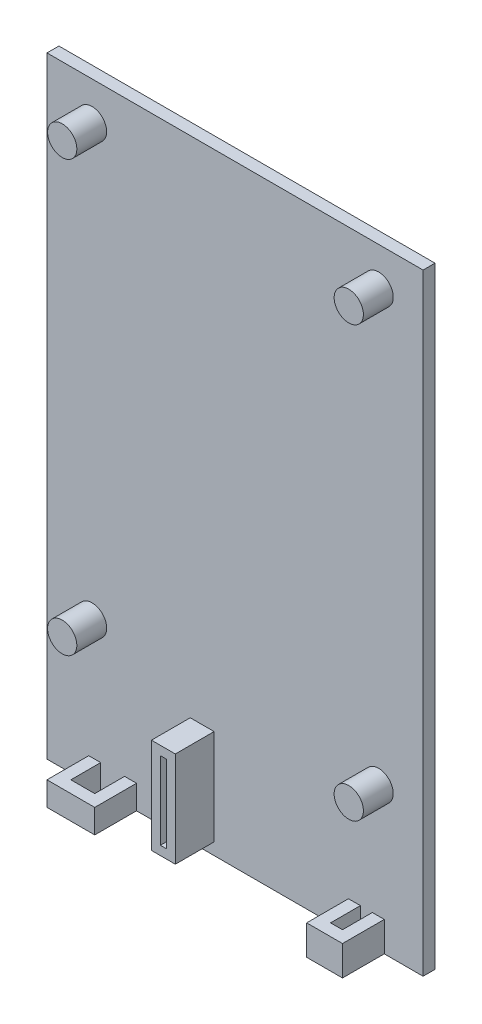
SolidWorks part; units mm, degrees
ref_plane "Přední rovina" through (0, 0, 0) normal (0, 0, 1) x (1, 0, 0)
ref_plane "Horní rovina" through (0, 0, 0) normal (0, 1, 0) x (1, 0, 0)
ref_plane "Pravá rovina" through (0, 0, 0) normal (1, 0, 0) x (0, 0, -1)
sketch "Skica1" plane through (0, 0, 0) normal (0, 0, 1) x (1, 0, 0)
  line L0 (13, -102.45) -> (13, -115.45)
  line L1 (0, 0) -> (63, 0)
  line L2 (0, 0) -> (0, -102.45)
  line L3 (0, -102.45) -> (13, -102.45)
  line L4 (63, 0) -> (63, -102.45)
  line L5 (13, -115.45) -> (50, -115.45)
  line L6 (50, -115.45) -> (50, -102.45)
  line L7 (50, -102.45) -> (63, -102.45)
  dimension "D1" = 102.45
  dimension "D2" = 63
  dimension "D3" = 13
  dimension "D4" = 13
  dimension "D5" = 13
extrude "Přidat vysunutím1" add sketch "Skica1" along normal blind 2
sketch "Skica3" plane through (0, 0, 2) normal (0, 0, 1) x (1, 0, 0)
  line L0 (63, -102.45) -> (63, 0) construction
  line L1 (63, 0) -> (0, 0) construction
  circle A0 centre (7.55, -6.45) radius 2.45
  circle A1 centre (7.55, -78.45) radius 2.45
  circle A2 centre (55.55, -78.45) radius 2.45
  circle A3 centre (55.55, -6.45) radius 2.45
  dimension "D1" = 4.9
  dimension "D2" = 48
  dimension "D4" = 7.45
  dimension "D5" = 6.45
  dimension "D3" = 72
extrude "Přidat vysunutím3" add sketch "Skica3" along normal blind 5
sketch "Skica4" plane through (0, 0, 2) normal (0, 0, 1) x (1, 0, 0)
  line L4 (63, 0) -> (63, -102.45)
  line L5 (3, -3) -> (60, -3)
  line L8 (60, -3) -> (60, -102.45)
  line L10 (60, -102.45) -> (63, -102.45)
  line L12 (0, 0) -> (0, -102.45)
  line L13 (0, 0) -> (63, 0)
  line L17 (3, -3) -> (3, -102.45)
  line L18 (0, -102.45) -> (13, -102.45) construction
  line L19 (3, -102.45) -> (0, -102.45)
  dimension "D1" = 3
  dimension "D2" = 3
  dimension "D3" = 3
extrude "Přidat vysunutím4" add sketch "Skica4" along normal blind 37.5
sketch "Skica8" plane through (60, 0, 0) normal (-1, 0, 0) x (0, 0, 1)
  line L0 (39.5, -3) -> (2, -3) construction
  line L1 (2, -54) -> (12, -54)
  line L2 (2, -54) -> (2, -44)
  line L3 (2, -44) -> (12, -44)
  line L4 (12, -54) -> (12, -44)
  line L5 (2, -3) -> (2, -102.45) construction
  dimension "D1" = 10
  dimension "D2" = 10
  dimension "D3" = 41
extrude "Odebrat vysunutím2" cut sketch "Skica8" against normal through all
sketch "Skica10" plane through (0, 0, 0) normal (-1, 0, 0) x (0, 0, 1)
  line L1 (12, -82) -> (39.5, -82)
  line L2 (12, -82) -> (12, -3)
  line L3 (12, -3) -> (39.5, -3)
  line L4 (39.5, -82) -> (39.5, -3)
  line L5 (39.5, 0) -> (39.5, -102.45) construction
  line L6 (0, 0) -> (0, -102.45) construction
  line L7 (39.5, 0) -> (0, 0) construction
  dimension "D1" = 3
  dimension "D2" = 12
  dimension "D3" = 79
extrude "Odebrat vysunutím3" cut sketch "Skica10" against normal up to surface (3 mm away) up to face at (3, -52.725, 20.75)
sketch "Skica11" plane through (0, 0, 2) normal (0, 0, 1) x (1, 0, 0)
  line L0 (3, -82) -> (60, -82)
  line L1 (3, -102.45) -> (3, -3) construction
  line L2 (60, -54) -> (60, -102.45) construction
  line L3 (60, -82) -> (60, -102.45)
  line L4 (60, -102.45) -> (50, -102.45)
  line L5 (50, -102.45) -> (50, -115.45)
  line L6 (50, -115.45) -> (13, -115.45)
  line L7 (13, -115.45) -> (13, -102.45)
  line L8 (13, -102.45) -> (13, -115.45) construction
  line L9 (3, -102.45) -> (13, -102.45) construction
  line L10 (13, -102.45) -> (3, -102.45)
  line L11 (3, -102.45) -> (3, -82)
  line L12 (3, -3) -> (60, -3) construction
  dimension "D1" = 79
extrude "Přidat vysunutím5" add sketch "Skica11" along normal blind 1
sketch "Skica12" plane through (0, 0, 3) normal (0, 0, 1) x (1, 0, 0)
  line L0 (3, -82) -> (3, -102.45) construction
  line L1 (15.5, -107.45) -> (21, -107.45)
  line L2 (15.5, -107.45) -> (15.5, -110.45)
  line L3 (15.5, -110.45) -> (21, -110.45)
  line L4 (21, -107.45) -> (21, -110.45)
  line L5 (15.5, -107.45) -> (21, -110.45) construction
  line L6 (15.5, -110.45) -> (21, -107.45) construction
  line L7 (13, -115.45) -> (50, -115.45) construction
  line L10 (15.5, -86.25) -> (15.5, -91.75)
  line L13 (15.5, -94.75) -> (15.5, -100.25)
  line L15 (11.2, -91.75) -> (15.5, -91.75)
  line L16 (11.2, -91.75) -> (11.2, -94.75)
  line L17 (11.2, -94.75) -> (15.5, -94.75)
  line L19 (15.5, -86.25) -> (46.5, -86.25)
  line L20 (46.5, -86.25) -> (46.5, -100.25)
  line L21 (46.5, -100.25) -> (15.5, -100.25)
  line L24 (60, -82) -> (3, -82) construction
  point P0 (18.25, -108.95)
  dimension "D1" = 3
  dimension "D2" = 5.5
  dimension "D4" = 5
  dimension "D5" = 3
  dimension "D6" = 14
  dimension "D7" = 31
  dimension "D8" = 4.3
  dimension "D9" = 7.2
  dimension "D10" = 12.5
  dimension "D11" = 5.5
  dimension "D12" = 4.25
sketch "Skica13" plane through (0, -102.45, 0) normal (0, -1, 0) x (1, 0, 0)
  line L1 (0, 39.5) -> (3, 39.5)
  line L2 (0, 39.5) -> (0, 3)
  line L3 (0, 3) -> (3, 3)
  line L4 (3, 39.5) -> (3, 3)
extrude "Odebrat vysunutím6" cut sketch "Skica13" against normal through all
sketch "Skica14" plane through (0, -102.45, 0) normal (0, -1, 0) x (1, 0, 0)
  line L1 (63, 39.5) -> (60, 39.5)
  line L2 (63, 39.5) -> (63, 3)
  line L3 (63, 3) -> (60, 3)
  line L4 (60, 39.5) -> (60, 3)
extrude "Odebrat vysunutím7" cut sketch "Skica14" against normal through all
sketch "Skica15" plane through (3, 0, 0) normal (-1, 0, 0) x (0, 0, 1)
  line L1 (39.5, 0) -> (3, 0)
  line L2 (39.5, 0) -> (39.5, -3)
  line L3 (39.5, -3) -> (3, -3)
  line L4 (3, 0) -> (3, -3)
extrude "Odebrat vysunutím8" cut sketch "Skica15" against normal through all
sketch "Skica19" plane through (0, 0, 3) normal (0, 0, 1) x (1, 0, 0)
  line L1 (13, -115.45) -> (50, -115.45)
  line L2 (13, -115.45) -> (13, -102.45)
  line L3 (13, -102.45) -> (50, -102.45)
  line L4 (50, -115.45) -> (50, -102.45)
extrude "Odebrat vysunutím9" cut sketch "Skica19" against normal through all
sketch "Skica20" plane through (0, 0, 3) normal (0, 0, 1) x (1, 0, 0)
  line L0 (0, -102.45) -> (63, -102.45)
  line L1 (63, -102.45) -> (63, 0)
  line L2 (63, 0) -> (0, 0)
  line L3 (0, 0) -> (0, -102.45)
  line L4 (3, -3) -> (3, -82)
  line L5 (3, -82) -> (60, -82)
  line L6 (60, -82) -> (60, -3)
  line L7 (60, -3) -> (3, -3)
extrude "Odebrat vysunutím10" cut sketch "Skica20" against normal blind 1
sketch "Skica22" plane through (0, 0, 2) normal (0, 0, 1) x (1, 0, 0)
  line L0 (0, -102.45) -> (63, -102.45) construction
  line L1 (7, -102.45) -> (15, -102.45)
  line L2 (7, -102.45) -> (7, -98.45)
  line L3 (7, -98.45) -> (15, -98.45)
  line L4 (15, -102.45) -> (15, -98.45)
  line L5 (0, 0) -> (0, -102.45) construction
  line L6 (50.5, -102.45) -> (56.5, -102.45)
  line L7 (50.5, -102.45) -> (50.5, -97.45)
  line L8 (50.5, -97.45) -> (56.5, -97.45)
  line L9 (56.5, -102.45) -> (56.5, -97.45)
  dimension "D1" = 8
  dimension "D2" = 4
  dimension "D3" = 35.5
  dimension "D4" = 7
  dimension "D5" = 6
  dimension "D6" = 5
extrude "Přidat vysunutím6" add sketch "Skica22" along normal blind 7
sketch "Skica23" plane through (0, -102.45, 0) normal (0, -1, 0) x (1, 0, 0)
  line L7 (15, 2) -> (50.5, 2) construction
  line L8 (9, 7) -> (13, 7)
  line L9 (9, 7) -> (9, 2)
  line L10 (9, 2) -> (13, 2)
  line L11 (13, 7) -> (13, 2)
  line L12 (15, 9) -> (15, 2) construction
  line L16 (56.5, 2) -> (63, 2) construction
  line L17 (52.5, 7) -> (54.5, 7)
  line L18 (52.5, 7) -> (52.5, 2)
  line L19 (52.5, 2) -> (54.5, 2)
  line L20 (54.5, 7) -> (54.5, 2)
  line L21 (50.5, 9) -> (50.5, 2) construction
  dimension "D1" = 4
  dimension "D2" = 5
  dimension "D3" = 0
  dimension "D4" = 2
  dimension "D5" = 0
  dimension "D6" = 2
  dimension "D7" = 2
  dimension "D8" = 5
extrude "Odebrat vysunutím12" cut sketch "Skica23" against normal blind 5
sketch "Skica25" plane through (0, 0, 2) normal (0, 0, 1) x (1, 0, 0)
  line L0 (50.5, -97.45) -> (50.5, -102.45) construction
  line L1 (25.5, -85.95) -> (26.5, -85.95)
  line L2 (25.5, -85.95) -> (25.5, -98.95)
  line L3 (25.5, -98.95) -> (26.5, -98.95)
  line L4 (26.5, -85.95) -> (26.5, -98.95)
  line L5 (24, -84.45) -> (28, -84.45)
  line L6 (24, -84.45) -> (24, -100.45)
  line L7 (24, -100.45) -> (28, -100.45)
  line L8 (28, -84.45) -> (28, -100.45)
  line L9 (15, -102.45) -> (50.5, -102.45) construction
  dimension "D1" = 1.5
  dimension "D2" = 1.5
  dimension "D3" = 1.5
  dimension "D4" = 1.5
  dimension "D5" = 1
  dimension "D6" = 13
  dimension "D7" = 24
  dimension "D8" = 2
extrude "Přidat vysunutím8" add sketch "Skica25" along normal blind 6.5
